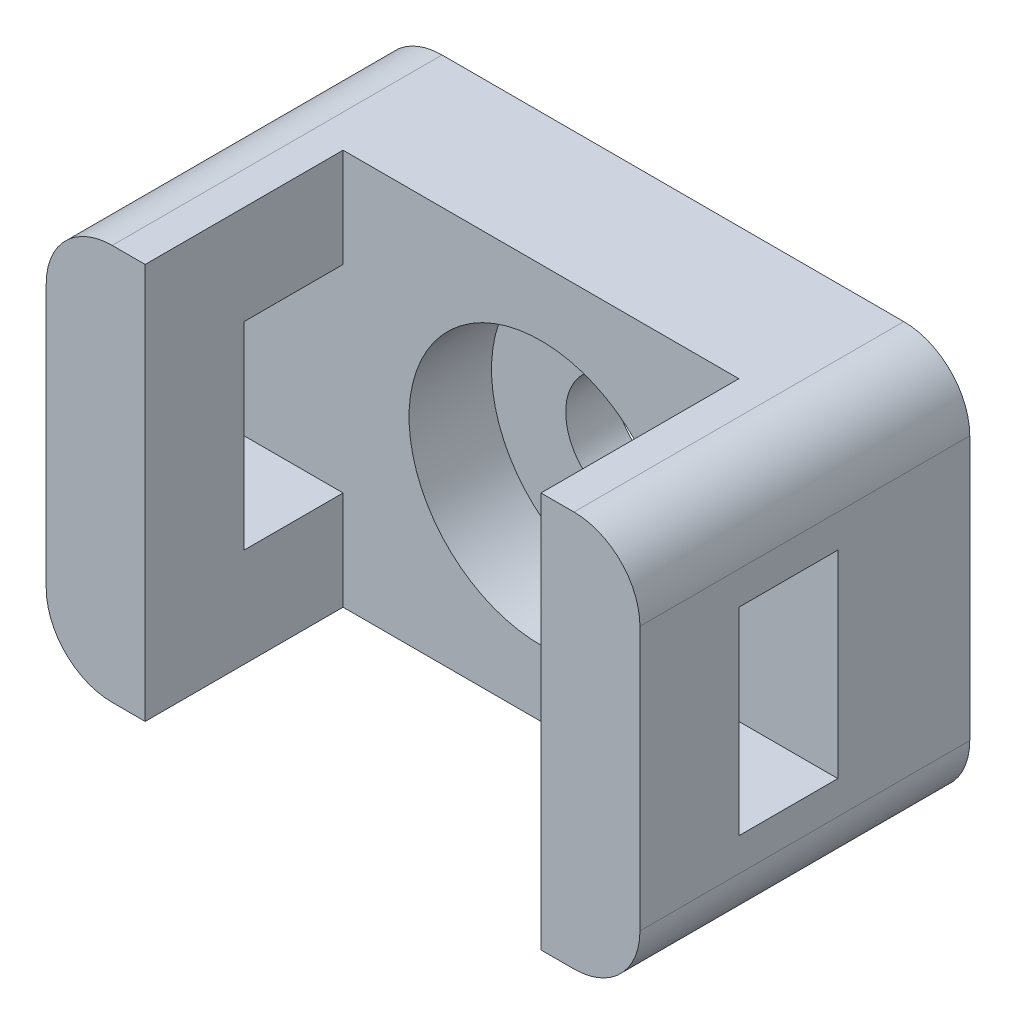
SolidWorks part; units mm, degrees
material "3D printed plastic"
ref_plane "Front Plane" through (0, 0, 0) normal (0, 0, 1) x (1, 0, 0)
ref_plane "Top Plane" through (0, 0, 0) normal (0, 1, 0) x (1, 0, 0)
ref_plane "Right Plane" through (0, 0, 0) normal (1, 0, 0) x (0, 0, -1)
sketch "Sketch1" plane through (0, 0, 0) normal (0, 0, 1) x (1, 0, 0)
  line L0 (-9, 6) -> (9, -6) construction
  line L1 (-9, 6) -> (9, 6)
  line L2 (-9, 6) -> (-9, -6)
  line L3 (-9, -6) -> (9, -6)
  line L4 (9, 6) -> (9, -6)
  line L5 (9, -6) -> (9, -5.6325) construction
  dimension "D1" = 18
  dimension "D2" = 12
extrude "Boss-Extrude1" add sketch "Sketch1" along normal blind 4
sketch "Sketch2" plane through (9, 0, 0) normal (1, 0, 0) x (0, 0, -1)
  line L0 (-4, -6) -> (-4, 6) construction
  line L1 (-4, 6) -> (-10, 6)
  line L2 (-4, 6) -> (-4, 3)
  line L3 (-4, -6) -> (-10, -6)
  line L4 (-10, 6) -> (-10, -6)
  line L5 (-4, -3) -> (-4, -6)
  line L6 (-4, 3) -> (-7, 3)
  line L8 (-4, -3) -> (-7, -3)
  line L9 (-7, 3) -> (-7, -3)
  dimension "D1" = 6
  dimension "D2" = 3
  dimension "D3" = 3
extrude "Boss-Extrude2" add sketch "Sketch2" against normal blind 3
mirror "Mirror1" about plane through (0, 0, 0) normal (1, 0, 0) of "Boss-Extrude2"
sketch "Sketch3" plane through (0, 0, 4) normal (0, 0, 1) x (1, 0, 0)
  circle A0 centre (0, 0) radius 1.75
  dimension "D1" = 3.5
extrude "Cut-Extrude1" cut sketch "Sketch3" against normal through all
sketch "Sketch4" plane through (0, 0, 4) normal (0, 0, 1) x (1, 0, 0)
  circle A0 centre (0, 0) radius 4
  dimension "D1" = 8
extrude "Cut-Extrude2" cut sketch "Sketch4" against normal blind 2.5
fillet "Fillet1" radius 2 4 edges at (-9, -6, 5) (9, -6, 5) (-9, 6, 5) (9, 6, 5)
